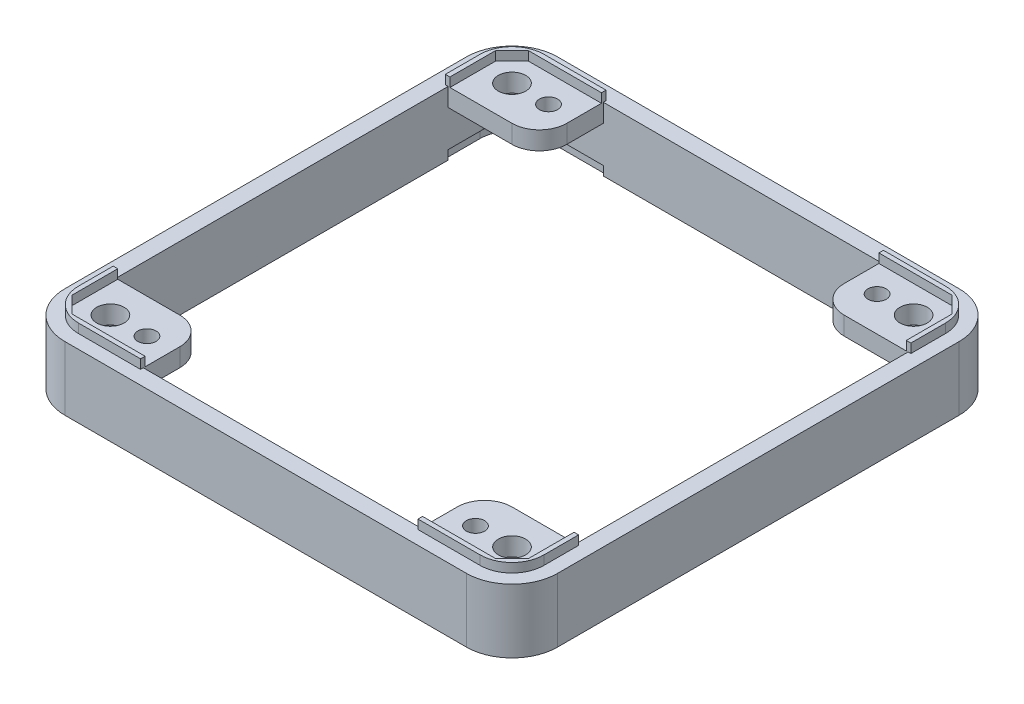
SolidWorks part; units mm, degrees
ref_plane "正面" through (0, 0, 0) normal (0, 0, 1) x (1, 0, 0)
ref_plane "平面" through (0, 0, 0) normal (0, 1, 0) x (1, 0, 0)
ref_plane "右側面" through (0, 0, 0) normal (1, 0, 0) x (0, 0, -1)
sketch "ｽｹｯﾁ7" plane through (0, 0, 0) normal (0, 1, 0) x (1, 0, 0)
  line L0 (22, 25.2) -> (0, 25.2)
  line L1 (0, 25.2) -> (0, 27)
  line L2 (0, 27) -> (22, 27)
  line L3 (25.2, 22) -> (25.2, 0)
  line L4 (25.2, 0) -> (27, 0)
  line L5 (27, 0) -> (27, 22)
  arc A0 (22, 25.2) -> (25.2, 22) centre (22, 22) cw
  arc A1 (22, 27) -> (27, 22) centre (22, 22) cw
  dimension "D1" = 3.2
  dimension "D2" = 5
  dimension "D3" = 22
  dimension "D4" = 22
  dimension "D5" = 1.8
  dimension "D6" = 1.8
  dimension "D7" = 22
  dimension "D8" = 22
extrude "ﾎﾞｽ - 押し出し2" add sketch "ｽｹｯﾁ7" along normal blind 7
ref_plane "平面1" through (0, 0, 0) normal (1, 0, 0) x (0, 0, -1)
ref_plane "平面2" through (0, 0, 0) normal (0, 0, 1) x (1, 0, 0)
sketch "ｽｹｯﾁ8" plane through (0, 7, 0) normal (0, 1, 0) x (1, 0, 0)
  line L0 (15.2, 21.2) -> (15.2, 25.2)
  line L1 (0, 25.2) -> (22, 25.2) construction
  line L2 (18.2, 18.2) -> (25.2, 18.2)
  line L3 (25.2, 22) -> (25.2, 0) construction
  line L4 (22, 25.2) -> (15.2, 25.2)
  line L5 (25.2, 18.2) -> (25.2, 22)
  arc A0 (15.2, 21.2) -> (18.2, 18.2) centre (18.2, 21.2) ccw
  arc A1 (25.2, 22) -> (22, 25.2) centre (22, 22) ccw
  arc A2 (25.2, 22) -> (22, 25.2) centre (22, 22) ccw construction
  dimension "D1" = 3
  dimension "D2" = 4
  dimension "D3" = 7
extrude "ﾎﾞｽ - 押し出し3" add sketch "ｽｹｯﾁ8" against normal blind 2
sketch "ｽｹｯﾁ10" plane through (0, 7, 0) normal (0, 1, 0) x (1, 0, 0)
  line L0 (25, 23.2) -> (25, 18.2)
  line L1 (18.2, 18.2) -> (25.2, 18.2) construction
  line L2 (25.5, 22) -> (25.5, 18.2)
  line L3 (25.5, 18.2) -> (25, 18.2)
  line L4 (23.2, 25) -> (15.2, 25)
  line L5 (15.2, 25.2) -> (15.2, 21.2) construction
  line L6 (15.2, 25) -> (15.2, 25.5)
  line L7 (15.2, 25.5) -> (22, 25.5)
  line L8 (27, 0) -> (27, 22) construction
  line L9 (22, 27) -> (0, 27) construction
  line L10 (23.2, 25) -> (25, 23.2)
  arc A0 (22, 25.5) -> (25.5, 22) centre (22, 22) cw
  dimension "D1" = 3.5
  dimension "D2" = 1.8
  dimension "D3" = 1.5
  dimension "D4" = 1.5
  dimension "D5" = 1.8
  dimension "D6" = 0.5
  dimension "D7" = 0.5
extrude "ﾎﾞｽ - 押し出し4" add sketch "ｽｹｯﾁ10" along normal blind 1
sketch "ｽｹｯﾁ11" plane through (0, 7, 0) normal (0, 1, 0) x (1, 0, 0)
  line L0 (25, 23.2) -> (25, 18.2) construction
  line L1 (15.2, 25) -> (23.2, 25) construction
  circle A0 centre (22, 22) radius 1.5
  circle A1 centre (18, 22) radius 1
  dimension "D3" = 3
  dimension "D6" = 2
  dimension "D1" = 3
  dimension "D2" = 3
  dimension "D4" = 7
  dimension "D5" = 3
extrude "ｶｯﾄ - 押し出し2" cut sketch "ｽｹｯﾁ11" against normal up to surface (2 mm away) up to face at (20.1736, 5, -21.6736)
sketch "ｽｹｯﾁ12" plane through (0, 0, 0) normal (0, -1, 0) x (-1, 0, 0)
  line L0 (-22, 25) -> (-15.2, 25)
  line L1 (-15.2, 25) -> (-15.2, 25.5)
  line L2 (-15.2, 25.5) -> (-22, 25.5)
  line L3 (-25.5, 22) -> (-25.5, 18.2)
  line L4 (-25.5, 18.2) -> (-25, 18.2)
  line L5 (-25, 18.2) -> (-25, 22)
  line L6 (-27, 0) -> (-27, 22) construction
  line L7 (-22, 27) -> (0, 27) construction
  arc A0 (-25.5, 22) -> (-22, 25.5) centre (-22, 22) cw
  arc A1 (-25, 22) -> (-22, 25) centre (-22, 22) cw
  dimension "D1" = 3
  dimension "D2" = 3.5
  dimension "D3" = 1.5
  dimension "D4" = 1.5
  dimension "D5" = 6.8
  dimension "D6" = 3.8
extrude "ｶｯﾄ - 押し出し3" cut sketch "ｽｹｯﾁ12" against normal blind 1
mirror "ﾐﾗｰ1" about plane through (0, 0, 0) normal (1, 0, 0) of bodies 110
mirror "ﾐﾗｰ2" about plane through (0, 0, 0) normal (0, 0, 1) of bodies 111
